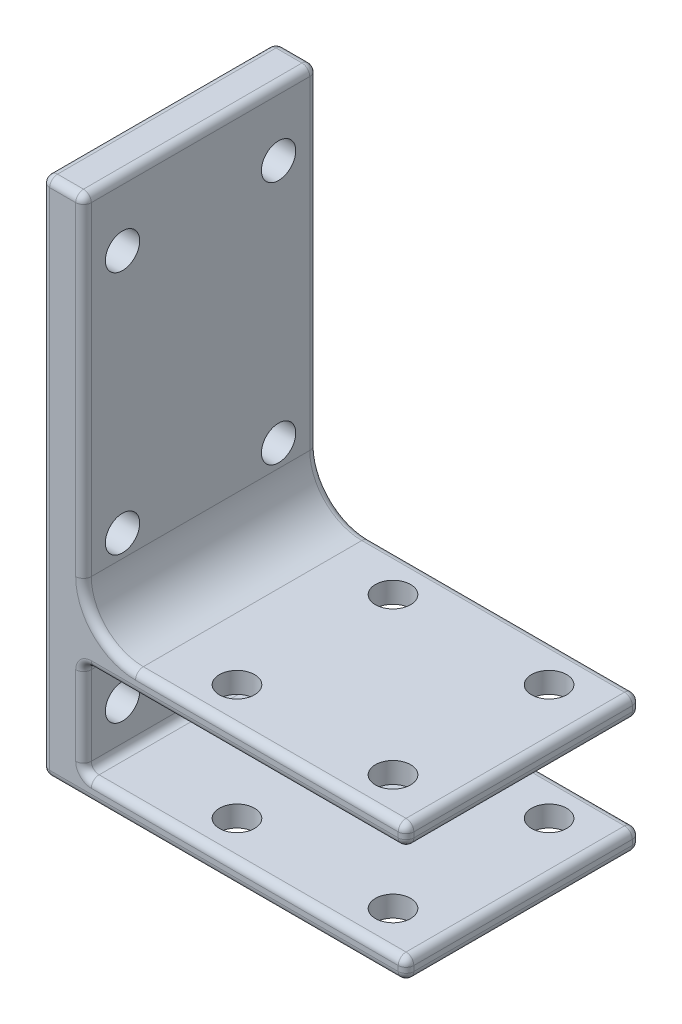
SolidWorks part; units mm, degrees
material "Nylon 6/10"
ref_plane "Front Plane" through (0, 0, 0) normal (0, 0, 1) x (1, 0, 0)
ref_plane "Top Plane" through (0, 0, 0) normal (0, 1, 0) x (1, 0, 0)
ref_plane "Right Plane" through (0, 0, 0) normal (1, 0, 0) x (0, 0, -1)
sketch "Sketch1" plane through (0, 0, 0) normal (0, 0, 1) x (1, 0, 0)
  line L0 (0, 0) -> (0, 100)
  line L1 (0, 100) -> (8, 100)
  line L2 (8, 100) -> (8, 4)
  line L3 (8, 4) -> (70, 4)
  line L4 (70, 4) -> (70, 0)
  line L5 (70, 0) -> (0, 0)
  dimension "D1" = 4
  dimension "D2" = 70
  dimension "D3" = 8
  dimension "D4" = 100
extrude "base" add sketch "Sketch1" along normal blind 45
sketch "Sketch2" plane through (8, 0, 0) normal (1, 0, 0) x (0, 0, -1)
  line L0 (-45, 4) -> (-45, 100) construction
  line L1 (-45, 26.25) -> (0, 26.25)
  line L2 (-45, 26.25) -> (-45, 22.25)
  line L3 (-45, 22.25) -> (0, 22.25)
  line L4 (0, 26.25) -> (0, 22.25)
  line L5 (0, 4) -> (0, 100) construction
  line L6 (-45, 4) -> (0, 4) construction
  dimension "D1" = 4
  dimension "D2" = 18.25
extrude "top skin" add sketch "Sketch2" along normal up to surface (62 mm away) up to face at (70, 2, 22.5)
hole_wizard "slider bolt hole pattern" positions "Sketch3" profile "Sketch4" hole size "M6" standard "ANSI Metric" end condition through all
sketch "Sketch3" plane through (8, 0, 0) normal (1, 0, 0) x (0, 0, -1)
  line L1 (-37.5, 87.5) -> (-7.5, 87.5)
  line L2 (-37.5, 87.5) -> (-37.5, 12.5)
  line L3 (-37.5, 12.5) -> (-7.5, 12.5)
  line L4 (-7.5, 87.5) -> (-7.5, 12.5)
  line L5 (-22.5, 12.5) -> (-22.5, 0) construction
  line L6 (-45, 0) -> (0, 0) construction
  line L8 (-22.5, 87.5) -> (-22.5, 100) construction
  line L9 (-45, 100) -> (0, 100) construction
  point P0 (-37.5, 87.5)
  point P1 (-7.5, 12.5)
  point P60 (-37.5, 12.5)
  point P61 (-7.5, 87.5)
  point P87 (-37.5, 40.5)
  point P89 (-7.5, 40.5)
  dimension "D1" = 75
  dimension "D2" = 30
  dimension "D3" = 28
sketch "Sketch4" plane through (8, 87.5, 37.5) normal (0, 1, 0) x (0, 0, -1)
  line L0 (0, 0) -> (0, 8)
  line L1 (0, 8) -> (3.3, 8)
  line L2 (3.3, 8) -> (3.3, 0)
  line L5 (3.3, 0) -> (0, 0)
  line L11 (0, -6.35) -> (0, 107.95) construction
  dimension "Thru Hole Dia." = 6.6
  dimension "Thru Hole Depth" = 8
hole_wizard "desktop bolt hole pattern" positions "Sketch5" profile "Sketch6" hole size "1/4" standard "ANSI Inch" end condition through all
sketch "Sketch5" plane through (0, 26.25, 0) normal (0, 1, 0) x (1, 0, 0)
  line L1 (30, -7.5) -> (60, -7.5)
  line L2 (30, -7.5) -> (30, -37.5)
  line L3 (30, -37.5) -> (60, -37.5)
  line L4 (60, -7.5) -> (60, -37.5)
  line L5 (60, -22.5) -> (70, -22.5)
  line L6 (70, -45) -> (70, 0) construction
  point P1 (30, -7.5)
  point P2 (60, -37.5)
  point P97 (30, -37.5)
  point P98 (60, -7.5)
  dimension "D2" = 30
  dimension "D1" = 10
  dimension "D3" = 30
sketch "Sketch6" plane through (30, 26.25, 7.5) normal (1, 0, 0) x (0, 0, 1)
  line L0 (0, 0) -> (0, 26.25)
  line L1 (0, 26.25) -> (3.3782, 26.25)
  line L2 (3.3782, 26.25) -> (3.3782, 0)
  line L5 (3.3782, 0) -> (0, 0)
  line L11 (0, -6.35) -> (0, 107.95) construction
  dimension "Thru Hole Dia." = 6.7564
  dimension "Thru Hole Depth" = 26.25
fillet "visible corner fillet" radius 10 1 edges at (8, 26.25, 22.5)
fillet "break other corners" radius 1.5 31 edges at (70, 0, 22.5) (70, 4, 22.5) (70, 26.25, 22.5) (70, 22.25, 22.5) (70, 2, 0) (39, 4, 0) (8, 13.125, 0) (39, 22.25, 0) (70, 24.25, 0) (44, 26.25, 0) (10.9289, 29.1789, 0) (8, 68.125, 0) (4, 100, 0) (35, 0, 0) (0, 100, 22.5) (0, 0, 22.5) (0, 50, 0) (0, 50, 45) (4, 100, 45) (8, 68.125, 45) (10.9289, 29.1789, 45) (44, 26.25, 45) (70, 24.25, 45) (39, 22.25, 45) (8, 13.125, 45) (39, 4, 45) (70, 2, 45) (35, 0, 45) (8, 4, 22.5) (8, 22.25, 22.5) (8, 100, 22.5)
equation "\"board_thickness\" = 18mm"
equation "\"way_width\"= 75mm"
equation "\"way_thickness\"= 50mm"
equation "\"radial_clearance\"= 0.1mm"
equation "\"slider_width\"= \"way_width\"-2* \"radial_clearance\""
equation "\"slider_thickness\" = \"way_thickness\" - 2 * \"radial_clearance\""
equation "\"column_width\"= \"way_width\" + 2 * \"board_thickness\""
equation "\"boxway_slot_width\" = 50mm"
equation "\"keeper_rail_width\" = (\"column_width\" - \"boxway_slot_width\")/2"
equation "\"slider_length\" = 125mm"
equation "\"nut_diameter\"= 22mm"
equation "\"nut_length\"= 15mm"
equation "\"leadscrew_diameter\"= 10mm"
equation "\"leadscrew_radial_clearance\"= 1mm"
equation "\"bearing_bolt_pattern_width\" = 30mm"
equation "\"bearing_bolt_pattern_height\" = 75mm"
equation "\"desktop_bolt_pattern_width\" = 30mm"
equation "\"desktop_bolt_pattern_height\" = 30mm"
equation "\"bearing_bolt_nut_counterbore_diameter\" = 12mm"
equation "\"bearing_bolt_nut_counterbore_depth\"= 10mm"
equation "\"desktop_depth\"= 500mm"
equation "\"desktop_width\"= 650mm"
equation "\"desktop_thickness\"= 18mm"
equation "\"leg_height\"=100mm"
equation "\"leg_width\"=18mm"
equation "\"leg_length\"=500mm"
equation "\"lap_joint_height\" = 50mm"
equation "\"lap_dowel_diameter\"= 8mm"
equation "\"lap_dowel_hole_z_spacing\"=30"
equation "\"skin_thicknes\"= 4"
equation "\"D1@Sketch1\"=\"skin_thicknes\""
equation "\"D1@Sketch2\"=\"skin_thicknes\""
equation "\"D2@Sketch2\"=\"desktop_thickness\" + 0.25"
equation "\"D1@Sketch3\"=\"bearing_bolt_pattern_height\""
equation "\"D2@Sketch3\"=\"bearing_bolt_pattern_width\""
equation "\"D2@Sketch5\"=\"desktop_bolt_pattern_width\""
equation "\"D3@Sketch5\"=\"desktop_bolt_pattern_height\""
